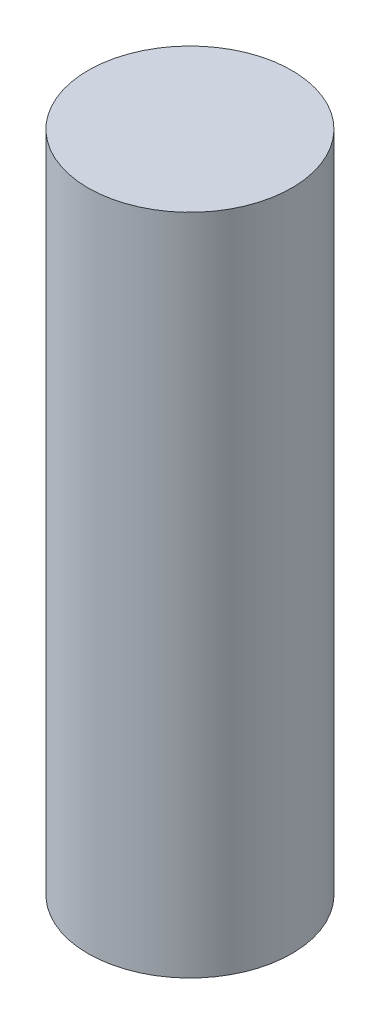
SolidWorks part; units mm, degrees
ref_plane "Front Plane" through (0, 0, 0) normal (0, 0, 1) x (1, 0, 0)
ref_plane "Top Plane" through (0, 0, 0) normal (0, 1, 0) x (1, 0, 0)
ref_plane "Right Plane" through (0, 0, 0) normal (1, 0, 0) x (0, 0, -1)
sketch "Sketch2" plane through (0, 0, 0) normal (0, 1, 0) x (1, 0, 0)
  circle A0 centre (0, 0) radius 10.775
  dimension "D1" = 21.55
extrude "Boss-Extrude1" add sketch "Sketch2" along normal blind 70.15
